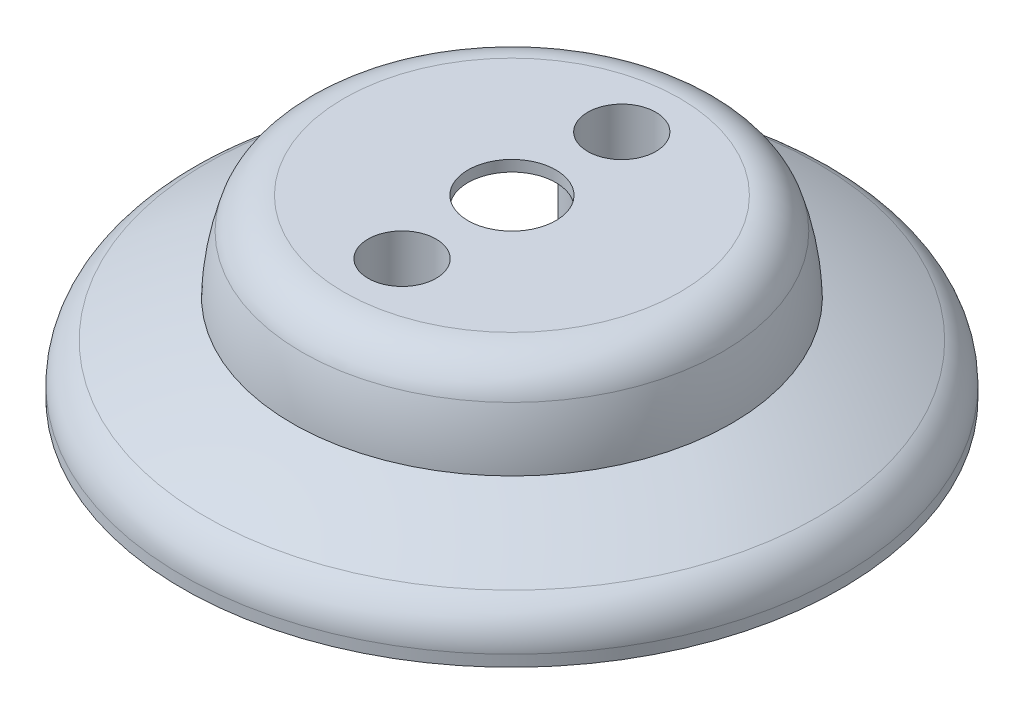
SolidWorks part; units mm, degrees
ref_plane "Alzado" through (0, 0, 0) normal (0, 0, 1) x (1, 0, 0)
ref_plane "Planta" through (0, 0, 0) normal (0, 1, 0) x (1, 0, 0)
ref_plane "Vista lateral" through (0, 0, 0) normal (1, 0, 0) x (0, 0, -1)
sketch "Croquis3" plane through (0, 0, 0) normal (0, 0, 1) x (1, 0, 0)
  line L0 (0, 0) -> (0, 8) construction
  line L1 (0, 8) -> (9, 8)
  line L2 (0, 0) -> (0, 8)
  line L3 (9.9936, 4) -> (0, 4) construction
  line L4 (0, 0) -> (15, 0)
  line L5 (15, 0) -> (15, 1.6942)
  arc A0 (9.9936, 4) -> (9, 8) centre (0, 3.6411) ccw
  arc A1 (15, 1.6942) -> (9.9936, 4) centre (0, -24.2865) ccw
  dimension "D3" = 20
  dimension "D4" = 60
  dimension "D1" = 8
  dimension "D2" = 9
  dimension "D6" = 4
  dimension "D7" = 15
revolve "Revolución1" add sketch "Croquis3" angle 360 about L2
sketch "Croquis4" plane through (0, 0, 0) normal (0, 0, 1) x (1, 0, 0)
  line L0 (0, 0.5) -> (0, 7.5)
  line L2 (0, 7.5) -> (0, 8) construction
  line L3 (9, 8) -> (-9, 8) construction
  line L8 (8.681, 7.5) -> (-8.681, 7.5)
  line L9 (-14.5, 0.5) -> (14.5, 0.5)
  line L10 (8.681, 7.5) -> (0, 7.5)
  line L11 (0, 0.5) -> (14.5, 0.5)
  line L12 (-14.5, 1.4039) -> (-14.5, 0.5)
  line L14 (14.5, 0.5) -> (14.5, 1.4039)
  line L15 (14.5, 0.5) -> (14.5, 1.4039)
  arc A8 (-9.5, 3.6419) -> (-14.5, 1.4039) centre (0, -24.2865) ccw
  arc A9 (-8.681, 7.5) -> (-9.5, 3.6419) centre (0, 3.6411) ccw
  arc A10 (14.5, 1.4039) -> (9.5, 3.6419) centre (0, -24.2865) ccw
  arc A11 (9.5, 3.6419) -> (8.681, 7.5) centre (0, 3.6411) ccw
  arc A14 (14.5, 1.4039) -> (9.5, 3.6419) centre (0, -24.2865) ccw
  arc A15 (9.5, 3.6419) -> (8.681, 7.5) centre (0, 3.6411) ccw
  dimension "D1" = 0.5
revolve "Cortar-Revolución1" cut sketch "Croquis4" angle 360 about L2
sketch "Croquis5" plane through (0, 8, 0) normal (0, 1, 0) x (1, 0, 0)
  circle A0 centre (0, 0) radius 2
  dimension "D1" = 4
extrude "Cortar-Extruir1" cut sketch "Croquis5" against normal blind 6
sketch "Croquis6" plane through (0, 0, 0) normal (0, -1, 0) x (1, 0, 0)
  circle A1 centre (0, 0) radius 14.5 construction
  circle A2 centre (0, 0) radius 14.5
extrude "Cortar-Extruir2" cut sketch "Croquis6" against normal blind 0.5
sketch "Croquis7" plane through (0, 7.5, 0) normal (0, -1, 0) x (1, 0, 0)
  line L0 (0, 0) -> (0, 8.681) construction
  line L1 (-8.681, 0) -> (8.681, 0) construction
  circle A0 centre (0, 0) radius 8.681 construction
  circle A1 centre (0, 5) radius 1.55
  circle A2 centre (0, 5) radius 2.05
  circle A3 centre (0, -5) radius 1.55
  circle A4 centre (0, -5) radius 2.05
  dimension "D1" = 3.1
  dimension "D3" = 0.5
  dimension "D2" = 5
extrude "Saliente-Extruir1" add sketch "Croquis7" along normal offset from surface (6.5 mm away) 1 up to face at (0, 0, -14.5)
sketch "Croquis8" plane through (0, 7.5, 0) normal (0, -1, 0) x (1, 0, 0)
  circle A0 centre (0, -5) radius 1.55 construction
  circle A1 centre (0, 5) radius 1.55 construction
  circle A2 centre (0, -5) radius 1.55
  circle A3 centre (0, 5) radius 1.55
extrude "Cortar-Extruir3" cut sketch "Croquis8" against normal blind 5.5
fillet "Redondeo1" radius 2 1 edges at (0, 8, -9)
fillet "Redondeo2" radius 2 1 edges at (0, 1.6942, -15)
